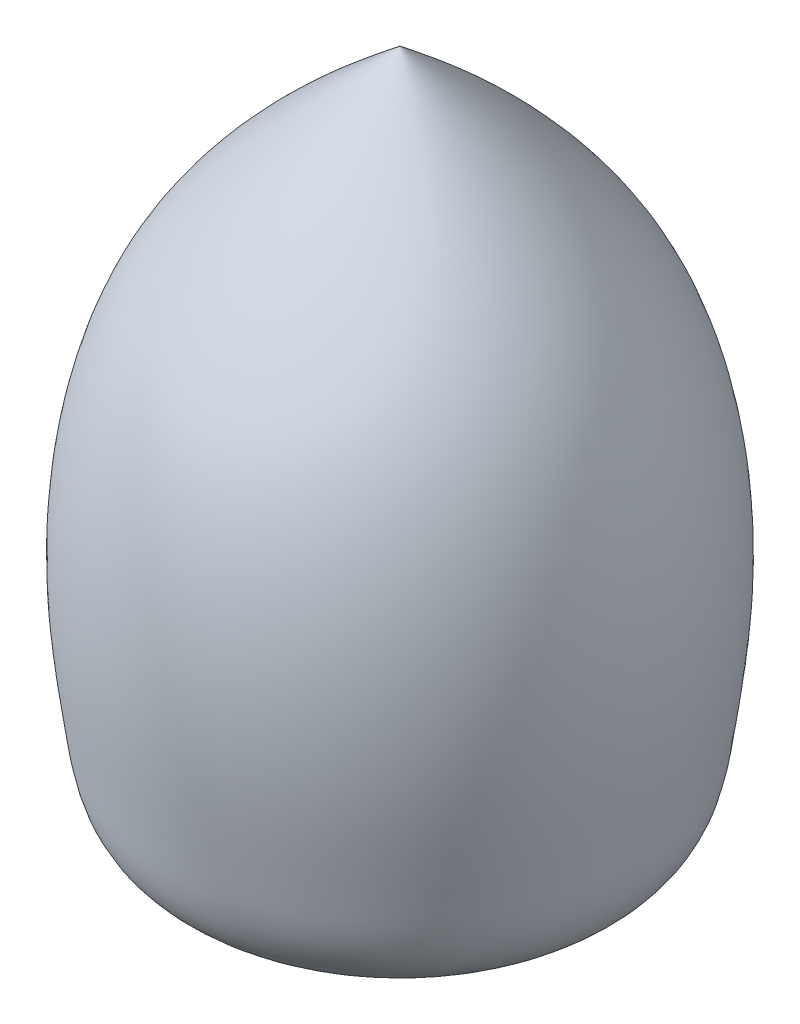
SolidWorks part; units mm, degrees
ref_plane "前基準面" through (0, 0, 0) normal (0, 0, 1) x (1, 0, 0)
ref_plane "上基準面" through (0, 0, 0) normal (0, 1, 0) x (1, 0, 0)
ref_plane "右基準面" through (0, 0, 0) normal (1, 0, 0) x (0, 0, -1)
sketch "草圖1" plane through (0, 0, 0) normal (0, 0, 1) x (1, 0, 0)
  line L2 (0, 0) -> (0, 5.5) construction
  line L3 (0, 5.5) -> (2, 5.5) construction
  line L4 (2, 5.5) -> (2, 0) construction
  line L5 (2, 0) -> (0, 0) construction
  line L7 (0, 0) -> (0, 5.5)
  line L8 (0.8501, 0) -> (1.077, 0)
  spline S0 degree 3 poles (0.8501, 0) (0.7208, -0.0212) (0.5631, -0.0462) (0.2795, -0.0476) (0.1274, 0) (0, 0) knots 0 0 0 0 0.45647 0.55647 1 1 1 1
  spline S1 degree 3 poles (1.077, 0) (1.2067, 0.0058) (1.455, 0.0169) (1.8338, 0.3023) (1.9196, 0.908) (2.0839, 2.063) (1.8375, 3.9893) (0.6259, 4.9855) (0, 5.5) knots 0 0 0 0 0.057456 0.110025 0.197662 0.316902 0.647158 1 1 1 1
  dimension "D1" = 0.2269
  dimension "D3" = 2
  dimension "D4" = 5.5
revolve "旋轉1" add sketch "草圖1" angle 360 about L7
